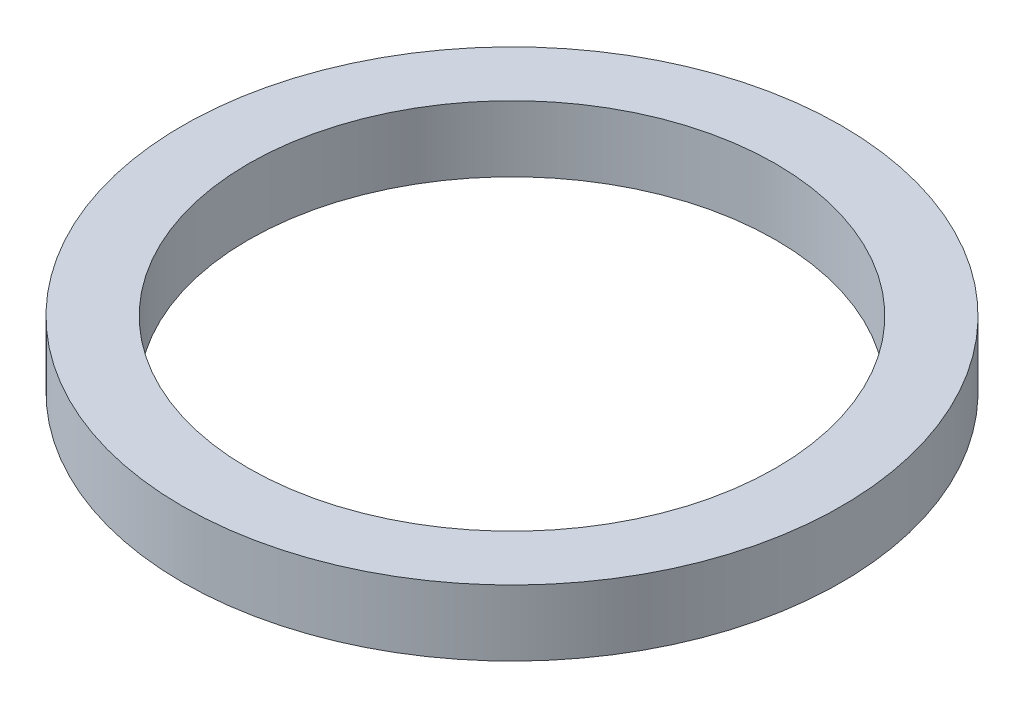
SolidWorks part; units mm, degrees
material "Rubber"
ref_plane "Front Plane" through (0, 0, 0) normal (0, 0, 1) x (1, 0, 0)
ref_plane "Top Plane" through (0, 0, 0) normal (0, 1, 0) x (1, 0, 0)
ref_plane "Right Plane" through (0, 0, 0) normal (1, 0, 0) x (0, 0, -1)
sketch "Sketch1" plane through (0, 0, 0) normal (0, 1, 0) x (1, 0, 0)
  circle A0 centre (0, 0) radius 15.875
  circle A1 centre (0, 0) radius 12.7
  dimension "D1" = 31.75
  dimension "D2" = 25.4
extrude "Boss-Extrude1" add sketch "Sketch1" along normal blind 3.175
